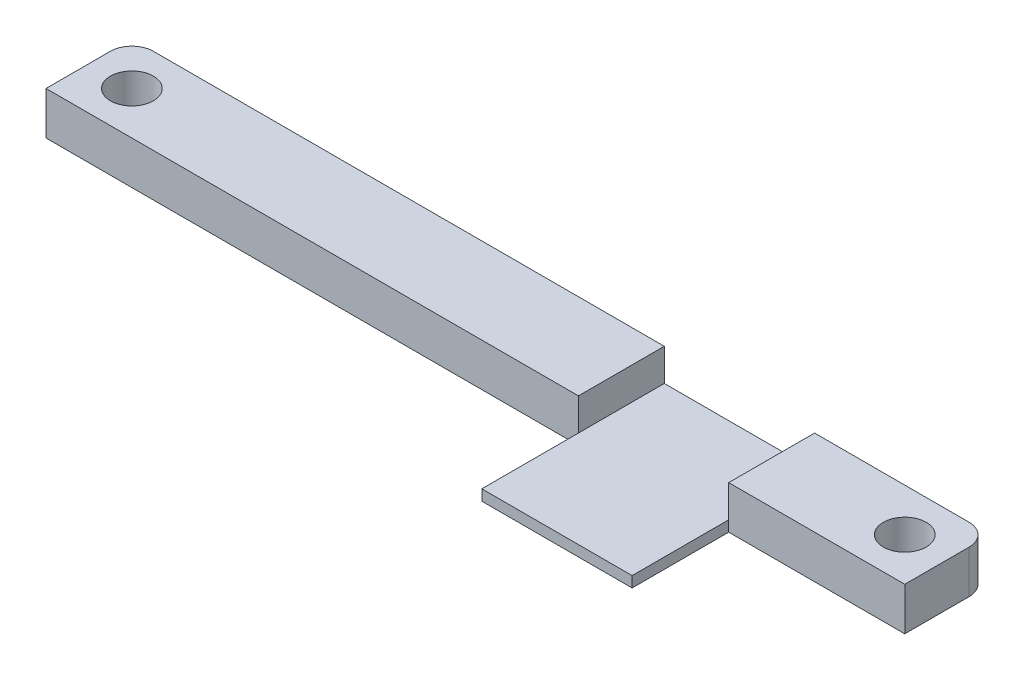
SolidWorks part; units mm, degrees
ref_plane "前视基准面" through (0, 0, 0) normal (0, 0, 1) x (1, 0, 0)
ref_plane "上视基准面" through (0, 0, 0) normal (0, 1, 0) x (1, 0, 0)
ref_plane "右视基准面" through (0, 0, 0) normal (1, 0, 0) x (0, 0, -1)
other "Configuration Table"
sketch "草图1" plane through (0, 0, 0) normal (0, 1, 0) x (1, 0, 0)
  line L0 (-40, -6) -> (0, -6)
  line L9 (-36, 6) -> (0, 6)
  line L10 (0, 6) -> (40, 6)
  line L11 (40, 6) -> (40, 0)
  line L12 (0, -6) -> (40, -6)
  line L13 (40, -6) -> (40, 0)
  line L17 (-36, 6) -> (-40, 6)
  line L18 (-40, 6) -> (-40, -6)
extrude "凸台-拉伸1" add sketch "草图1" along normal blind 12 contours L9 L10 L11 L13 L12 L0 L18 L17
sketch "草图2" plane through (0, 0, 6) normal (0, 0, 1) x (1, 0, 0)
  line L0 (0, 0) -> (-36, 0)
  line L1 (-40, 0) -> (40, 0) construction
  line L2 (0, 0) -> (36, 0)
  line L3 (-40, 0) -> (-40, 4)
  line L4 (-40, 12) -> (-40, 0) construction
  line L5 (-40, 4) -> (-32, 4)
  line L6 (-32, 4) -> (-32, 12)
  line L7 (-40, 12) -> (40, 12) construction
  line L8 (40, 0) -> (40, 4)
  line L9 (40, 12) -> (40, 0) construction
  line L10 (40, 4) -> (32, 4)
  line L11 (32, 4) -> (32, 12)
  line L12 (-32, 4) -> (-32, 8)
  line L13 (-32, 8) -> (32, 8)
  line L14 (-32, 4) -> (-28, 4)
  line L15 (32, 4) -> (28, 4)
  line L16 (-28, 4) -> (-28, 0)
  line L17 (-28, 4) -> (-28, 8)
  line L18 (28, 4) -> (28, 0)
  line L19 (28, 4) -> (28, 8)
  line L20 (28, 8) -> (-28, 8)
  line L21 (-28, 0) -> (28, 0)
  line M9 (-40, 0) -> (40, 0)
  line M10 (40, 0) -> (40, 12)
  line M11 (40, 12) -> (-40, 12)
  line M12 (-40, 12) -> (-40, 0)
extrude "切除-拉伸1" cut sketch "草图2" against normal blind 12 contours L18 L19 L13 L17 L16 L0 M9 | L5 L6 M11 M12 | L11 L10 M10 M11
sketch "草图3" plane through (0, 12, 0) normal (0, 1, 0) x (1, 0, 0)
  line L0 (40, 6) -> (40, 4)
  line L1 (40, 6) -> (40, -6) construction
  line L4 (38, 6) -> (40, 6)
  line L5 (-40, 6) -> (-38, 6)
  line L6 (-40, 6) -> (-32, 6) construction
  line L8 (-40, 6) -> (-40, -6) construction
  line L9 (-40, 6) -> (-40, 4)
  circle A0 centre (-36, 2) radius 2
  circle A1 centre (36, 2) radius 2
  arc A2 (40, 4) -> (38, 6) centre (38, 4) ccw
  arc A3 (-40, 4) -> (-38, 6) centre (-38, 4) cw
extrude "切除-拉伸2" cut sketch "草图3" against normal blind 12 contours L9 A3 L5 | A0 | A2 L0 L4 | A1
sketch "草图4" plane through (0, 12, 0) normal (0, 1, 0) x (1, 0, 0)
  line L0 (-21.1, 0) -> (-21.1, 6)
  line L1 (-12.1, 0) -> (12.08, 0)
  line L2 (-21.1, 6) -> (-16.6, 6)
  line L3 (32, 6) -> (-32, 6) construction
  line L5 (-32, -6) -> (32, -6) construction
  line L6 (12.08, -1) -> (12.08, -6)
  line L7 (-12.1, 6) -> (12.08, 6)
  line L8 (-21.1, 0) -> (-21.1, -6)
  line L9 (-21.1, -6) -> (-16.6, -6)
  line L10 (-12.1, 0) -> (-12.1, -6)
  line L11 (-12.1, -6) -> (-16.6, -6)
  line L13 (-12.1, 6) -> (-16.6, 6)
  line L14 (12.08, 0) -> (12.08, -1)
  line L18 (12.08, -6) -> (16.6, -6)
  line L20 (12.08, 6) -> (16.6, 6)
  line L21 (21.12, -1) -> (21.12, 6)
  line L22 (21.12, 6) -> (16.6, 6)
  line L23 (21.12, -1) -> (21.12, -6)
  line L24 (21.12, -6) -> (16.6, -6)
extrude "切除-拉伸3" cut sketch "草图4" against normal blind 1 contours L0 L2 L13 L7 L20 L22 L21 L23 L24 L18 L6 L14 L1 L10 L11 L9 L8
sketch "草图5" plane through (0, 12, 0) normal (0, 1, 0) x (1, 0, 0)
  line L0 (-36, 2) -> (-36, -2)
  line L1 (-36, -2) -> (40, -2)
  line L2 (40, 4) -> (40, -6) construction
  line L3 (40, -2) -> (-40, -2)
  line L4 (-40, 4) -> (-40, -6) construction
  line L5 (-40, -2) -> (-40, -6)
  line L6 (-40, -6) -> (40, -6)
  line L7 (40, -6) -> (40, -2)
extrude "切除-拉伸4" cut sketch "草图5" against normal blind 20
sketch "草图6" plane through (0, 12, 0) normal (0, 1, 0) x (1, 0, 0)
  line L0 (12.08, 0) -> (12.08, 6)
  line L1 (21.12, 6) -> (-21.1, 6) construction
  line L2 (12.08, 6) -> (-21.1, 6)
  line L3 (-21.1, 6) -> (-21.1, -2)
  line L4 (-21.1, -2) -> (-12.1, -2)
  line L5 (-21.1, -2) -> (-12.1, -2) construction
  line L6 (-12.1, -2) -> (-12.1, 0)
  line L7 (-12.1, 0) -> (12.08, 0)
extrude "凸台-拉伸2" add sketch "草图6" against normal blind 1
sketch "草图7" plane through (0, 12, 0) normal (0, 1, 0) x (1, 0, 0)
  line L0 (21.12, -2) -> (32, -2) construction
  line L1 (21.12, 6) -> (21.32, 6)
  line L2 (21.12, 6) -> (21.12, -2)
  line L3 (21.12, -2) -> (21.32, -2)
  line L4 (21.32, 6) -> (21.32, -2)
  line L5 (-32, -2) -> (12.08, -2) construction
  line L6 (12.08, 6) -> (11.88, 6)
  line L7 (12.08, 6) -> (12.08, -2)
  line L8 (12.08, -2) -> (11.88, -2)
  line L9 (11.88, 6) -> (11.88, -2)
extrude "切除-拉伸5" cut sketch "草图7" against normal blind 1
sketch "草图8" plane through (0, 12, 0) normal (0, 1, 0) x (1, 0, 0)
  line L0 (-32, -2) -> (-40, -2)
  line L1 (-40, -2) -> (-40, 4)
  line L4 (-38, 6) -> (-32, 6)
  line L5 (-32, 6) -> (-32, -2) construction
  line L6 (-38, 6) -> (-32, 6) construction
  line L7 (-32, 6) -> (-32, -2)
  line L8 (32, -2) -> (32, 6)
  line L9 (32, 6) -> (38, 6)
  line L12 (40, 4) -> (40, -2)
  line L13 (40, -2) -> (32, -2)
  arc A0 (-40, 4) -> (-38, 6) centre (-38, 4) cw
  arc A1 (-38, 6) -> (-40, 4) centre (-38, 4) ccw construction
  arc A2 (40, 4) -> (38, 6) centre (38, 4) ccw
  circle A3 centre (36, 2) radius 2
  circle A4 centre (-36, 2) radius 2
  line M18 (-32, 6) -> (-32, -2)
extrude "凸台-拉伸3" add sketch "草图8" against normal blind 4 contours A3 | A0 L1 L0 L4 A4 M18 | A2 L12 L13 L8 L9
sketch "草图9" plane through (0, 0, 2) normal (0, 0, 1) x (1, 0, 0)
  line L1 (-40, 0) -> (40, 0)
  line L2 (-40, 0) -> (-40, 8)
  line L3 (-40, 8) -> (40, 8)
  line L4 (40, 0) -> (40, 8)
extrude "切除-拉伸6" cut sketch "草图9" against normal blind 10
sketch "草图10" plane through (0, 12, 0) normal (0, 1, 0) x (1, 0, 0)
  line L0 (11.88, 6) -> (21.32, -2)
  line L1 (11.88, -2) -> (21.32, -2)
  line L2 (16.6, -2) -> (16.6, 2.9964)
  line L3 (16.6, 2.9964) -> (23.6, 2.9964)
  line L4 (16.6, 2.9964) -> (9.6, 2.9964)
  line L5 (9.6, 2.9964) -> (9.6, -2)
  line L6 (-40, -2) -> (11.88, -2) construction
  line L7 (23.6, 2.9964) -> (23.6, 6)
  line L8 (38, 6) -> (21.32, 6) construction
  line L10 (9.6, -2) -> (23.6, -2)
  line L11 (9.6, -2) -> (9.6, 6)
  line L12 (9.6, 6) -> (23.6, 6)
  line L13 (23.6, -2) -> (23.6, 6)
extrude "切除-拉伸7" cut sketch "草图10" against normal blind 2 contours L11 L10 L13 L12
sketch "草图11" plane through (0, 10, 0) normal (0, 1, 0) x (1, 0, 0)
  line L1 (9.6, -2) -> (23.6, -2)
  line L2 (9.6, -2) -> (9.6, -11)
  line L3 (9.6, -11) -> (23.6, -11)
  line L4 (23.6, -2) -> (23.6, -11)
extrude "凸台-拉伸4" add sketch "草图11" against normal blind 2 contours L2 L1 L4 L3
sketch "草图12" plane through (0, 0, -6) normal (0, 0, -1) x (-1, 0, 0)
  line L1 (-23.6, 10) -> (-9.6, 10)
  line L2 (-23.6, 10) -> (-23.6, 9)
  line L3 (-23.6, 9) -> (-9.6, 9)
  line L4 (-9.6, 10) -> (-9.6, 9)
extrude "切除-拉伸8" cut sketch "草图12" against normal blind 20
